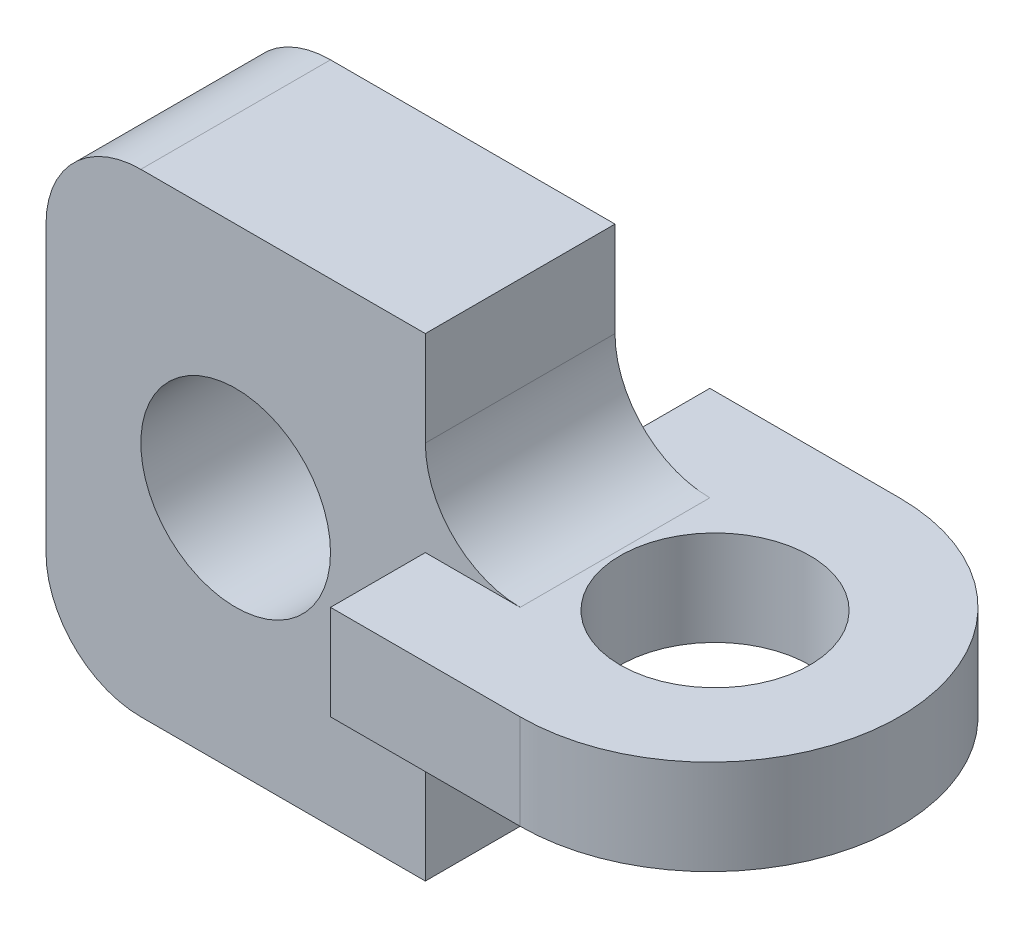
SolidWorks part; units mm, degrees
ref_plane "Front Plane" through (0, 0, 0) normal (0, 0, 1) x (1, 0, 0)
ref_plane "Top Plane" through (0, 0, 0) normal (0, 1, 0) x (1, 0, 0)
ref_plane "Right Plane" through (0, 0, 0) normal (1, 0, 0) x (0, 0, -1)
sketch "Sketch1" plane through (0, 0, 0) normal (0, 1, 0) x (1, 0, 0)
  line L0 (-0.5489, 20) -> (-20.5489, 20)
  line L1 (-20.5489, 20) -> (-20.5489, -20)
  line L2 (-20.5489, -20) -> (-0.5489, -20)
  circle A0 centre (0, 0) radius 10
  arc A1 (-0.5489, -20) -> (-0.5489, 20) centre (-0.5489, 0) ccw
  dimension "D1" = 40
  dimension "D2" = 20
extrude "Boss-Extrude1" add sketch "Sketch1" along normal blind 10
sketch "Sketch2" plane through (-20.5489, 0, 0) normal (-1, 0, 0) x (0, 0, 1)
  line L0 (0, 0) -> (0, 10) construction
  line L1 (-20, 10) -> (20, 10) construction
  line L3 (-10, 30) -> (10, 30)
  line L4 (-10, 30) -> (-10, -20)
  line L5 (-10, -20) -> (10, -20)
  line L6 (10, 30) -> (10, -20)
  line L7 (-10, 30) -> (10, -20) construction
  line L8 (-10, -20) -> (10, 30) construction
  point P6 (0, 5)
  dimension "D1" = 20
  dimension "D2" = 50
extrude "Boss-Extrude2" add sketch "Sketch2" along normal blind 40 contours L6 L5 L4 L3
sketch "Sketch3" plane through (0, 0, 10) normal (0, 0, 1) x (1, 0, 0)
  line L0 (-50.5489, 30) -> (-20.5489, 30)
  line L3 (-20.5489, 30) -> (-20.5489, 10)
  line L4 (-20.5489, 10) -> (19.4511, 10)
  line L5 (19.4511, 10) -> (19.4511, 0)
  line L6 (19.4511, 0) -> (-20.5489, 0)
  line L7 (-20.5489, 0) -> (-20.5489, -20)
  line L8 (-20.5489, -20) -> (-50.5489, -20)
  line L9 (-60.5489, -10) -> (-60.5489, 20)
  circle A0 centre (-40.5489, 5) radius 10
  arc A1 (-50.5489, -20) -> (-60.5489, -10) centre (-50.5489, -10) cw
  arc A2 (-60.5489, 20) -> (-50.5489, 30) centre (-50.5489, 20) cw
  point P20 (-60.5489, -20)
  point P23 (-60.5489, 30)
  dimension "D1" = 20
  dimension "D2" = 10
extrude "Cut-Extrude1" cut sketch "Sketch3" against normal blind 40 flip side to cut
sketch "Sketch4" plane through (0, 0, 10) normal (0, 0, 1) x (1, 0, 0)
  line L0 (-20.5489, 0) -> (-20.5489, -10)
  line L1 (-20.5489, 0) -> (-10.5489, 0)
  line L4 (-20.5489, 20) -> (-20.5489, 10)
  line L5 (-20.5489, 10) -> (-10.5489, 10)
  arc A0 (-20.5489, -10) -> (-10.5489, 0) centre (-10.5489, -10) cw
  arc A1 (-10.5489, 10) -> (-20.5489, 20) centre (-10.5489, 20) cw
  point P14 (-20.5489, 0)
  point P17 (-20.5489, 10)
  dimension "D1" = 10
extrude "Boss-Extrude3" add sketch "Sketch4" against normal blind 20
